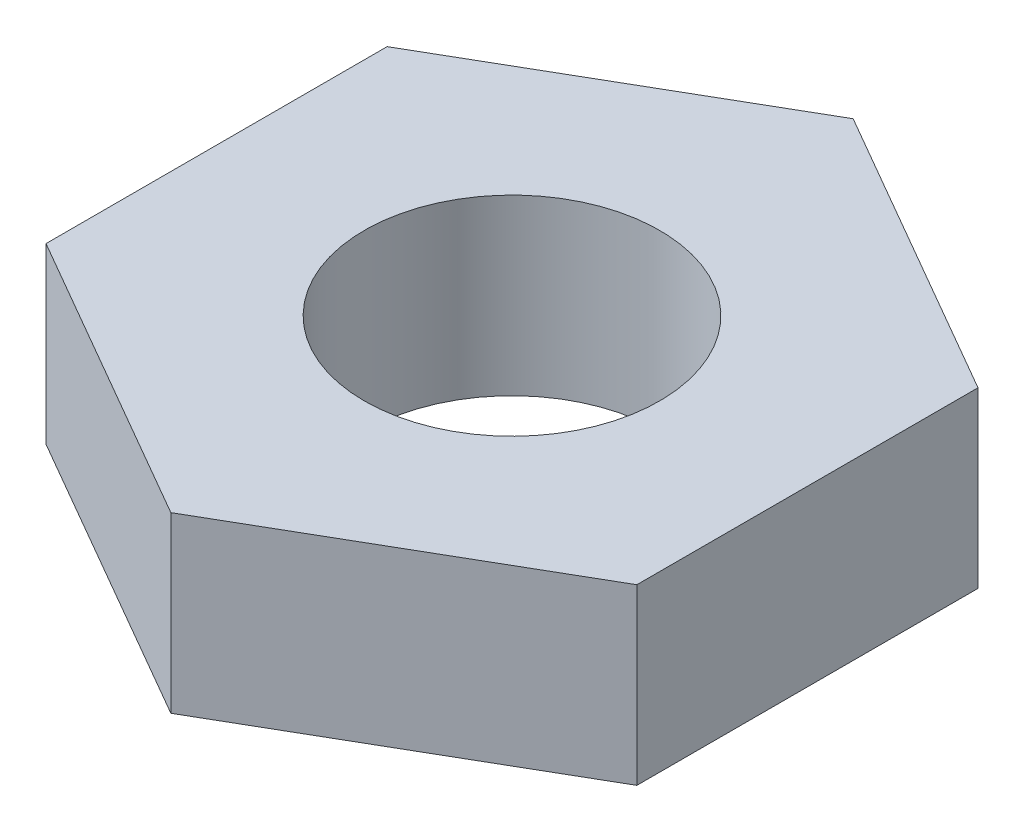
SolidWorks part; units mm, degrees
ref_plane "Front/Back" through (0, 0, 0) normal (0, 0, 1) x (1, 0, 0)
ref_plane "Top/Bottom" through (0, 0, 0) normal (0, 1, 0) x (1, 0, 0)
ref_plane "Right/Left" through (0, 0, 0) normal (1, 0, 0) x (0, 0, -1)
sketch "Nut sk" plane through (0, 0, 0) normal (0, 1, 0) x (1, 0, 0)
  line L0 (0, 0) -> (8.5, 0) construction
  line L1 (0, 0) -> (0, 9.815) construction
  line L2 (8.5, -4.9075) -> (8.5, 4.9075)
  line L3 (8.5, 4.9075) -> (0, 9.815)
  line L4 (-8.5, 4.9075) -> (0, 9.815)
  line L5 (-8.5, -4.9075) -> (-8.5, 4.9075)
  line L6 (-8.5, -4.9075) -> (0, -9.815)
  line L7 (8.5, -4.9075) -> (0, -9.815)
  circle A0 centre (0, 0) radius 4.25
  point P8 (-8.5, 0)
  dimension "Minor Diameter" = 8.5
  dimension "Angle" = 60
  dimension "A/F" = 17
  dimension "Across Corners" = 19.6299
extrude "Nut" add sketch "Nut sk" along normal blind 5
cosmetic thread "Thread" parameters "Major Diameter"=10
